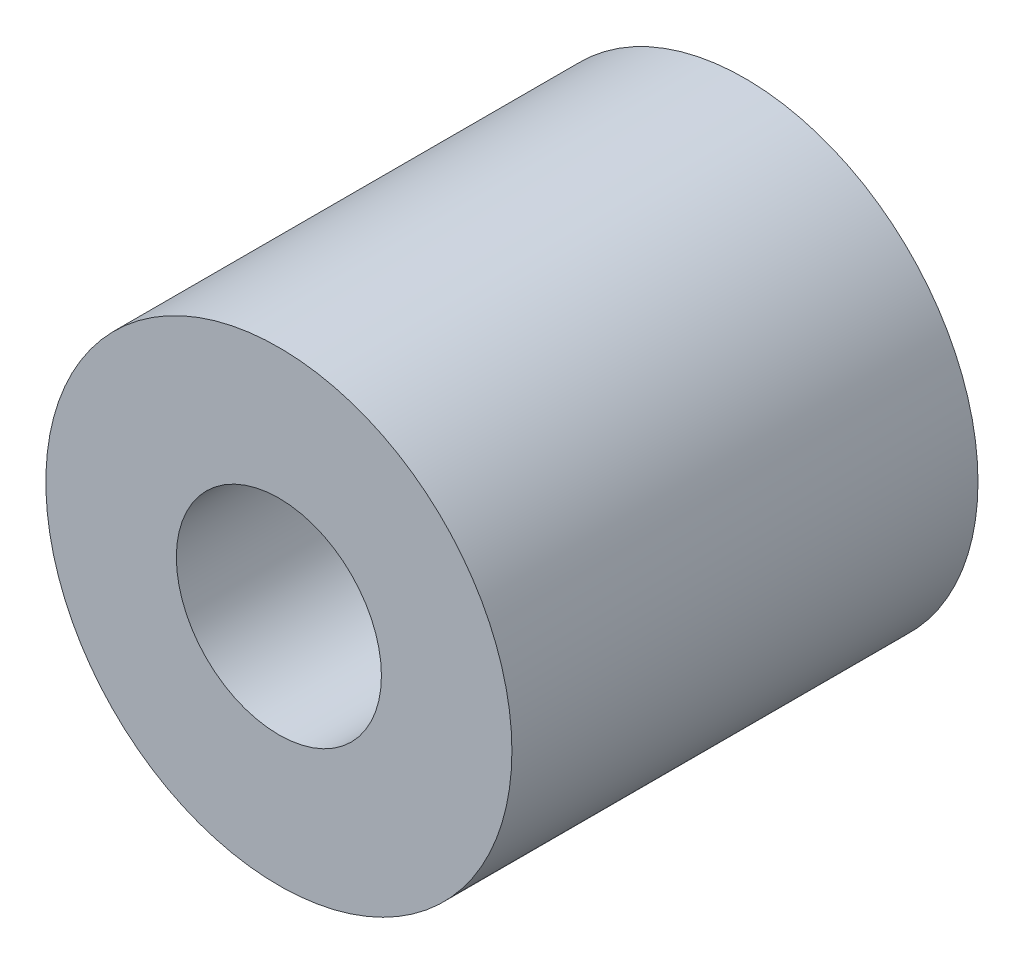
SolidWorks part; units mm, degrees
other "Preload Base Mounting Spacer"
ref_plane "Front Plane" through (0, 0, 0) normal (0, 0, 1) x (1, 0, 0)
ref_plane "Top Plane" through (0, 0, 0) normal (0, 1, 0) x (1, 0, 0)
ref_plane "Right Plane" through (0, 0, 0) normal (1, 0, 0) x (0, 0, -1)
sketch3d "Spacer ring sketch datum points"
  point P0 (-57.2917, -7, -51)
  point P1 (-47.2917, -7, -51)
  point P2 (-57.2917, 3, -51)
ref_plane "Spacer ring sketch plane" through (0, 0, -51) normal (0, 0, 1) x (1, 0, 0)
sketch "Spacer ring sketch" plane through (0, 0, -51) normal (0, 0, 1) x (1, 0, 0)
  circle A0 centre (-57.2917, -7) radius 5
  circle A1 centre (-57.2917, -7) radius 2.2
extrude "Spacer ring" add sketch "Spacer ring sketch" along normal blind 10 separate body
